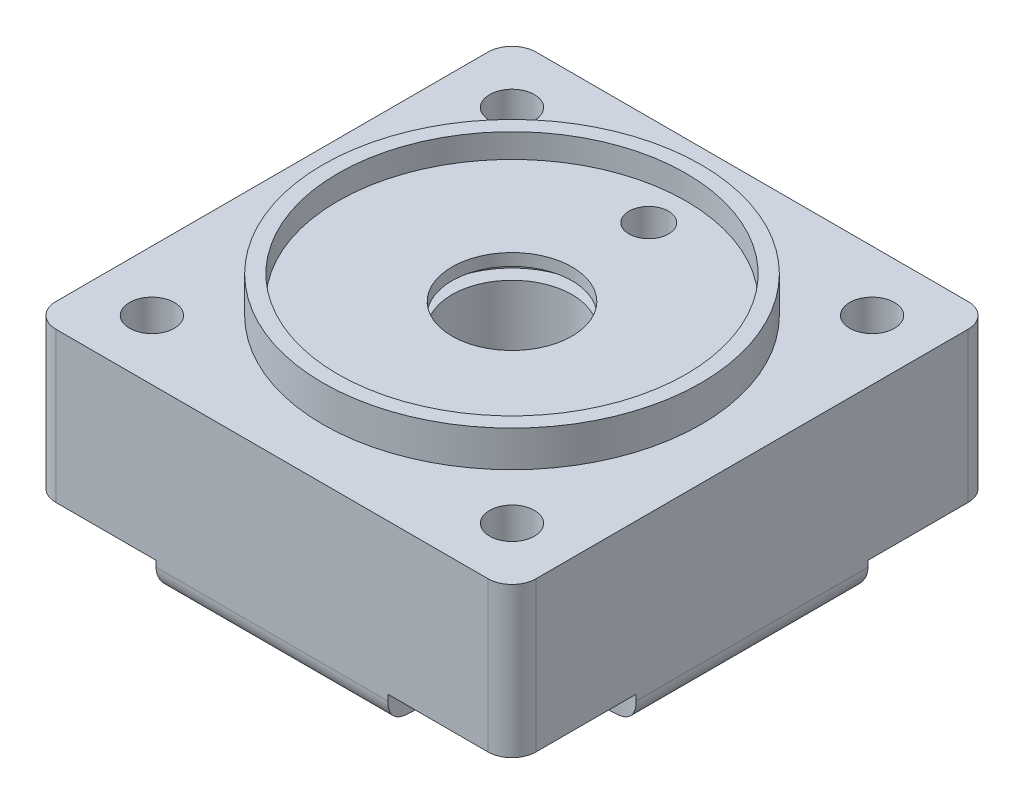
SolidWorks part; units mm, degrees
ref_plane "Plan de face" through (0, 0, 0) normal (0, 0, 1) x (1, 0, 0)
ref_plane "Plan de dessus" through (0, 0, 0) normal (0, 1, 0) x (1, 0, 0)
ref_plane "Plan de droite" through (0, 0, 0) normal (1, 0, 0) x (0, 0, -1)
sketch "Esquisse1" plane through (0, 0, 0) normal (0, 1, 0) x (1, 0, 0)
  circle A0 centre (0, 0) radius 31.5
  circle A1 centre (0, 0) radius 29
  dimension "D1" = 58
  dimension "D2" = 63
extrude "Boss.-Extru.1" add sketch "Esquisse1" along normal blind 6
sketch "Esquisse2" plane through (0, 0, 0) normal (0, 1, 0) x (1, 0, 0)
  circle A0 centre (0, 0) radius 29
extrude "Boss.-Extru.2" add sketch "Esquisse2" along normal blind 2
sketch "Esquisse3" plane through (0, 0, 0) normal (0, -1, 0) x (1, 0, 0)
  line L1 (-40, 40) -> (40, 40)
  line L2 (-40, 40) -> (-40, -40)
  line L3 (-40, -40) -> (40, -40)
  line L4 (40, 40) -> (40, -40)
  point P6 (20.2447, -0.3995)
  point P7 (20.2447, -2.1806)
  dimension "D1" = 80
  dimension "D2" = 80
  dimension "D3" = 40
  dimension "D4" = 40
extrude "Boss.-Extru.3" add sketch "Esquisse3" along normal blind 30
fillet "Congé1" radius 4 8 edges at (-40, -15, 40) (40, -15, 40) (40, -15, -40) (0, -30, 40) (40, -30, 0) (0, -30, -40) (-40, -15, -40) (-40, -30, 0)
sketch "Esquisse6" plane through (0, -30, 0) normal (0, -1, 0) x (1, 0, 0)
  circle A0 centre (0, 0) radius 20
  dimension "D1" = 40
extrude "Boss.-Extru.5" add sketch "Esquisse6" along normal blind 15
fillet "Congé3" radius 4 2 edges at (0, -45, -20) (0, -30, -20)
sketch "Esquisse7" plane through (0, -45, 0) normal (0, -1, 0) x (-1, 0, 0)
  circle A0 centre (0, 0) radius 10
  dimension "D1" = 20
extrude "Enlèv. mat.-Extru.2" cut sketch "Esquisse7" against normal through all
sketch "Esquisse8" plane through (0, -30, 0) normal (0, -1, 0) x (1, 0, 0)
  circle A0 centre (36, -36) radius 17.1708
extrude "Enlèv. mat.-Extru.3" cut sketch "Esquisse8" against normal blind 5
sketch "Esquisse9" plane through (0, -25, 0) normal (0, -1, 0) x (1, 0, 0)
  line L0 (40, -36) -> (40, -19.3016) construction
  line L1 (19.3016, -40) -> (36, -40) construction
  circle A0 centre (30, -30) radius 3.7319
  dimension "D1" = 10
  dimension "D2" = 10
extrude "Enlèv. mat.-Extru.4" cut sketch "Esquisse9" against normal through all contours A0
pattern_circular "Répétition circulaire1" count 4 over 360 about axis through (0, 0, 0) along (0, 1, 0) of "Enlèv. mat.-Extru.3", "Enlèv. mat.-Extru.4"
hole_wizard "Dégagement M61" positions "Esquisse11" profile "Esquisse10" hole size "M6" standard "ISO"
sketch "Esquisse11" plane through (0, 2, 0) normal (0, 1, 0) x (1, 0, 0)
  point P0 (0, 22.7846)
sketch "Esquisse10" plane through (0, 2, -22.7846) normal (1, 0, 0) x (0, 0, 1)
  line L0 (0, 0) -> (0, 21.9828)
  line L1 (0, 21.9828) -> (3.3, 20)
  line L2 (3.3, 20) -> (3.3, 0)
  line L5 (3.3, 0) -> (0, 0)
  line L10 (0, 21.9828) -> (-3.3, 20) construction
  line L11 (0, -6.35) -> (0, 107.95) construction
  dimension "Diamètre du perçage" = 6.6
  dimension "Profondeur du perçage" = 20
  dimension "Angle de pointe" = 118
hole_wizard "Dégagement M62" positions "Esquisse13" profile "Esquisse12" hole size "M6" standard "ISO"
sketch "Esquisse13" plane through (0, 0, -40) normal (0, 0, -1) x (-1, 0, 0)
  point P0 (0, -13.6359)
sketch "Esquisse12" plane through (0, -13.6359, -40) normal (1, 0, 0) x (0, 1, 0)
  line L0 (0, 0) -> (0, 21.9828)
  line L1 (0, 21.9828) -> (3.3, 20)
  line L2 (3.3, 20) -> (3.3, 0)
  line L5 (3.3, 0) -> (0, 0)
  line L10 (0, 21.9828) -> (-3.3, 20) construction
  line L11 (0, -6.35) -> (0, 107.95) construction
  dimension "Diamètre du perçage" = 6.6
  dimension "Profondeur du perçage" = 20
  dimension "Angle de pointe" = 118
sketch "Esquisse14" plane through (0, 0, -40) normal (0, 0, -1) x (-1, 0, 0)
  circle A0 centre (0, -13.6359) radius 6
  dimension "D1" = 12
extrude "Enlèv. mat.-Extru.5" cut sketch "Esquisse14" against normal blind 2
sketch "Esquisse15" plane through (0, 0, 0) normal (0, 1, 0) x (1, 0, 0)
  circle A0 centre (0, 0) radius 12.5
  dimension "D1" = 25
extrude "Enlèv. mat.-Extru.6" cut sketch "Esquisse15" against normal blind 2
